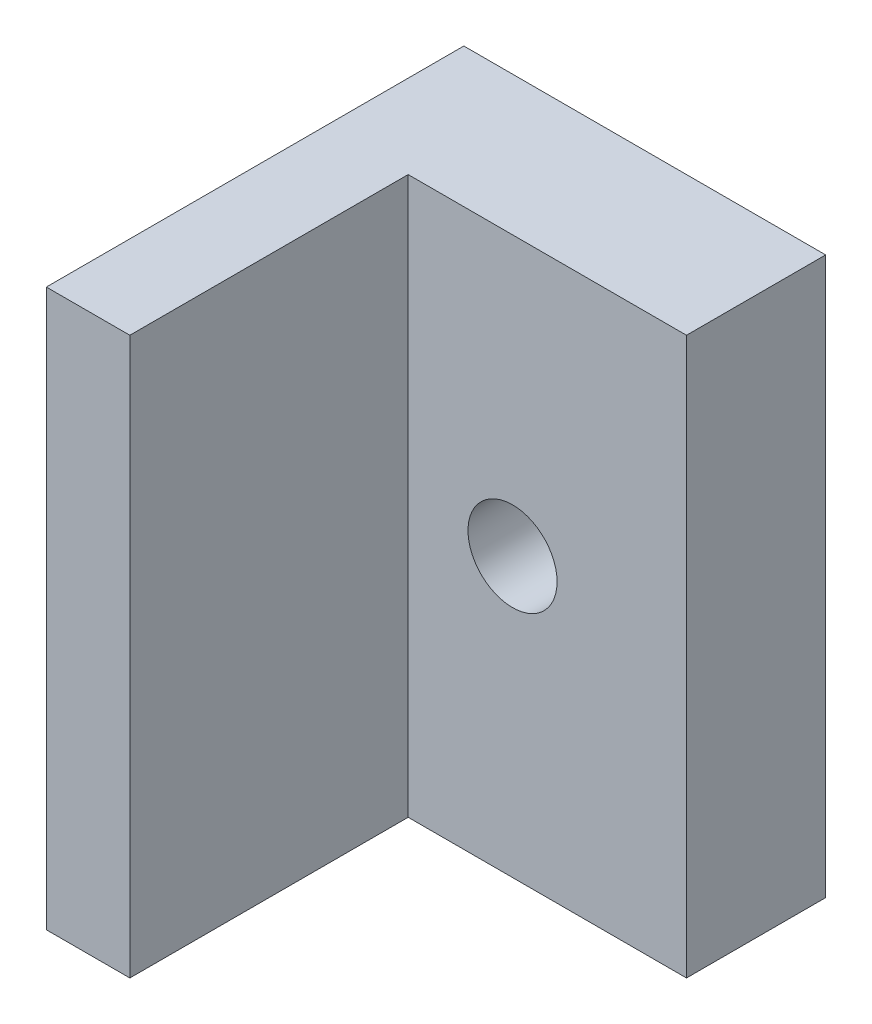
SolidWorks part; units mm, degrees
ref_plane "Płaszczyzna przednia" through (0, 0, 0) normal (0, 0, 1) x (1, 0, 0)
ref_plane "Płaszczyzna górna" through (0, 0, 0) normal (0, 1, 0) x (1, 0, 0)
ref_plane "Płaszczyzna prawa" through (0, 0, 0) normal (1, 0, 0) x (0, 0, -1)
sketch "Szkic1" plane through (0, 0, 0) normal (0, 0, 1) x (1, 0, 0)
  line L0 (35.75, -83.369) -> (35.75, 102.705) construction
  line L6 (-3.75, 10) -> (-6.75, 10)
  line L7 (-3.75, 10) -> (-3.75, -10)
  line L8 (-3.75, -10) -> (-6.75, -10)
  line L9 (-6.75, 10) -> (-6.75, -10)
  line L10 (-3.75, 10) -> (6.25, 10)
  line L11 (-3.75, 10) -> (-3.75, -10)
  line L12 (-3.75, -10) -> (6.25, -10)
  line L13 (6.25, 10) -> (6.25, -10)
  circle A0 centre (0, 0) radius 1.6
  circle A1 centre (71.5, 0) radius 1.6
  dimension "D1" = 71.5
  dimension "D2" = 3.2
  dimension "D3" = 39.5
  dimension "D4" = 35.75
  dimension "D5" = 20
  dimension "D6" = 10
  dimension "D7" = 3
  dimension "D8" = 10
extrude "Dodanie-wyciągnięcie1" add sketch "Szkic1" along normal blind 5 contours L13 L10 L7 L12 A0 | L6 L9 L8 L7
sketch "Szkic2" plane through (0, 0, 5) normal (0, 0, 1) x (1, 0, 0)
  line L0 (-6.75, -10) -> (6.25, -10) construction
  line L1 (-6.75, 10) -> (-3.75, 10)
  line L2 (-6.75, 10) -> (-6.75, -10)
  line L3 (-6.75, -10) -> (-3.75, -10)
  line L4 (-3.75, 10) -> (-3.75, -10)
  dimension "D1" = 3
extrude "Dodanie-wyciągnięcie2" add sketch "Szkic2" along normal blind 10
